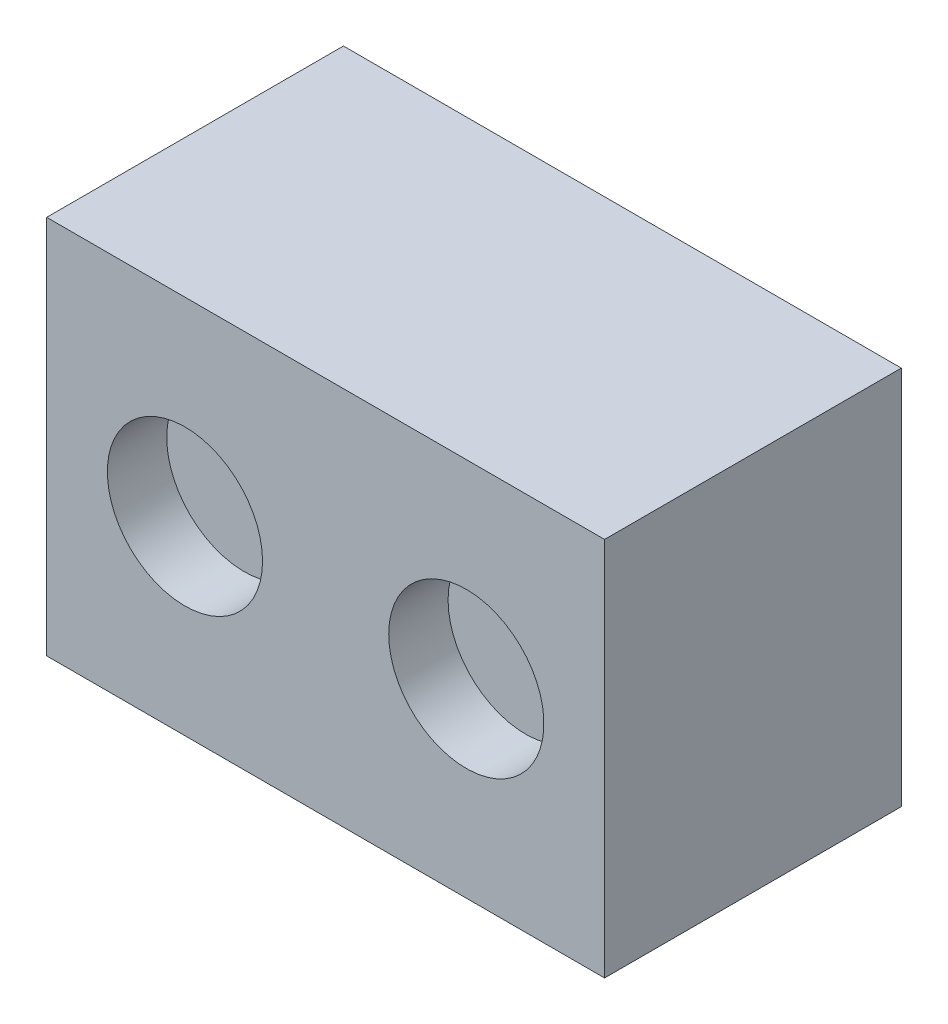
SolidWorks part; units mm, degrees
ref_plane "Alzado" through (0, 0, 0) normal (0, 0, 1) x (1, 0, 0)
ref_plane "Planta" through (0, 0, 0) normal (0, 1, 0) x (1, 0, 0)
ref_plane "Vista lateral" through (0, 0, 0) normal (1, 0, 0) x (0, 0, -1)
sketch "Croquis1" plane through (0, 0, 0) normal (0, 0, 1) x (1, 0, 0)
  line L1 (-9.4, 6.4) -> (9.4, 6.4)
  line L2 (-9.4, 6.4) -> (-9.4, -6.4)
  line L3 (-9.4, -6.4) -> (9.4, -6.4)
  line L4 (9.4, 6.4) -> (9.4, -6.4)
  line L5 (-9.4, 6.4) -> (9.4, -6.4) construction
  line L6 (-9.4, -6.4) -> (9.4, 6.4) construction
  point P0 (0, 0)
  dimension "D1" = 12.8
  dimension "D2" = 18.8
extrude "Saliente-Extruir1" add sketch "Croquis1" along normal blind 10
sketch "Croquis2" plane through (0, 0, 10) normal (0, 0, 1) x (1, 0, 0)
  line L0 (0, 6.4) -> (0, -6.4) construction
  line L1 (9.4, 6.4) -> (-9.4, 6.4) construction
  line L2 (-9.4, -6.4) -> (9.4, -6.4) construction
  circle A0 centre (-4.7407, 0) radius 2.6146
extrude "Cortar-Extruir1" cut sketch "Croquis2" against normal blind 2
mirror "Simetría1" about plane through (0, 0, 0) normal (1, 0, 0) of "Cortar-Extruir1"
